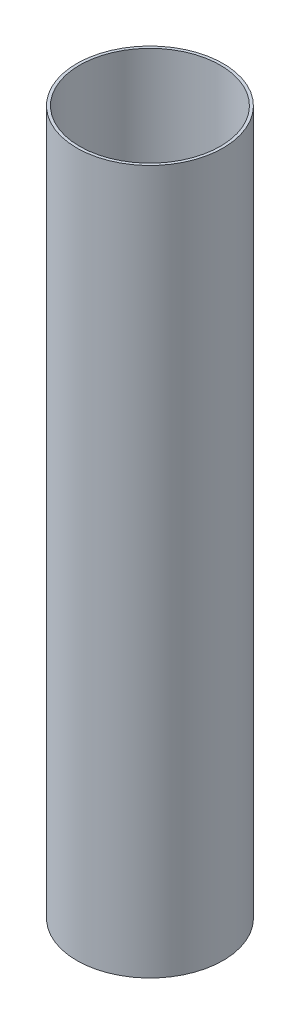
SolidWorks part; units mm, degrees
ref_plane "Front Plane" through (0, 0, 0) normal (0, 0, 1) x (1, 0, 0)
ref_plane "Top Plane" through (0, 0, 0) normal (0, 1, 0) x (1, 0, 0)
ref_plane "Right Plane" through (0, 0, 0) normal (1, 0, 0) x (0, 0, -1)
sketch "Sketch2" plane through (0, 0, 0) normal (0, 1, 0) x (1, 0, 0)
  circle A0 centre (0, 0) radius 38.1
  circle A1 centre (0, 0) radius 39.624
  dimension "D1" = 79.248
  dimension "D2" = 76.2
extrude "Boss-Extrude1" add sketch "Sketch2" along normal blind 381
